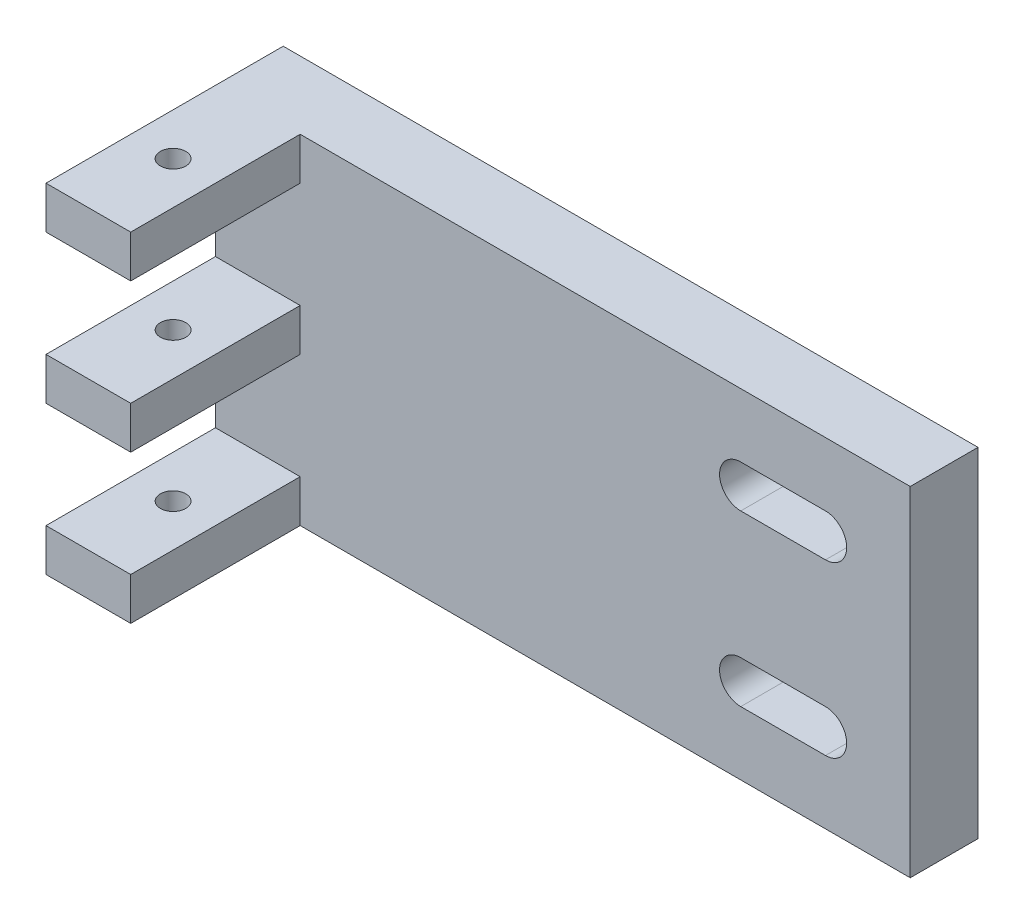
SolidWorks part; units mm, degrees
ref_plane "前视基准面" through (0, 0, 0) normal (0, 0, 1) x (1, 0, 0)
ref_plane "上视基准面" through (0, 0, 0) normal (0, 1, 0) x (1, 0, 0)
ref_plane "右视基准面" through (0, 0, 0) normal (1, 0, 0) x (0, 0, -1)
sketch "草图1" plane through (0, 0, 0) normal (0, 0, 1) x (1, 0, 0)
  line L0 (26.1842, 30.9079) -> (26.1842, -9.0921) construction
  line L1 (-25.8158, 30.9079) -> (46.1842, 30.9079)
  line L2 (-25.8158, 30.9079) -> (-25.8158, -9.0921)
  line L3 (-25.8158, -9.0921) -> (46.1842, -9.0921)
  line L4 (46.1842, 30.9079) -> (46.1842, -9.0921)
  line L7 (36.1842, 23.4079) -> (46.1842, 23.4079)
  line L8 (46.1842, 30.9079) -> (56.1842, 30.9079)
  line L9 (46.1842, 30.9079) -> (46.1842, -9.0921)
  line L10 (46.1842, -9.0921) -> (56.1842, -9.0921)
  line L11 (56.1842, 30.9079) -> (56.1842, -9.0921)
  line L12 (36.1842, 18.4079) -> (46.1842, 18.4079)
  line L13 (36.1842, 3.4079) -> (46.1842, 3.4079)
  line L14 (36.1842, -1.5921) -> (46.1842, -1.5921)
  circle A0 centre (36.1842, 20.9079) radius 2.5
  circle A1 centre (36.1842, 0.9079) radius 2.5
  circle A2 centre (46.1842, 20.9079) radius 2.5
  circle A3 centre (46.1842, 0.9079) radius 2.5
  dimension "D4" = 10
  dimension "D1" = 72
  dimension "D2" = 40
  dimension "D3" = 20
extrude "凸台-拉伸1" add sketch "草图1" along normal blind 8 contours L0 L1 L2 L3 | L1 L0 L3 L9 L14 A1 L13 L12 A0 L7 L4 | A3 L9 L10 L11 L8 L4 A2
sketch "草图3" plane through (0, 0, 8) normal (0, 0, 1) x (1, 0, 0)
  line L0 (-25.8158, 10.9079) -> (-25.8158, 13.4079) construction
  line L1 (-25.8158, 30.9079) -> (-15.8158, 30.9079)
  line L2 (-25.8158, 30.9079) -> (-25.8158, 25.9079)
  line L3 (-25.8158, 25.9079) -> (-15.8158, 25.9079)
  line L4 (-15.8158, 30.9079) -> (-15.8158, 25.9079)
  line L5 (-25.8158, -9.0921) -> (-15.8158, -9.0921)
  line L6 (-25.8158, -9.0921) -> (-25.8158, -4.0921)
  line L7 (-25.8158, -4.0921) -> (-15.8158, -4.0921)
  line L8 (-15.8158, -9.0921) -> (-15.8158, -4.0921)
  line L9 (-25.8158, 30.9079) -> (-25.8158, -9.0921) construction
  line L11 (-25.8158, 13.4079) -> (-15.8158, 13.4079)
  line L12 (-25.8158, 13.4079) -> (-25.8158, 8.4079)
  line L13 (-25.8158, 8.4079) -> (-15.8158, 8.4079)
  line L14 (-15.8158, 13.4079) -> (-15.8158, 8.4079)
  dimension "D1" = 5
  dimension "D2" = 10
  dimension "D3" = 10
  dimension "D4" = 5
  dimension "D5" = 2.5
  dimension "D6" = 5
  dimension "D7" = 10
extrude "凸台-拉伸3" add sketch "草图3" along normal blind 20 contours L2 L1 L4 L3 | L12 L11 L14 L13 | L6 L5 L8 L7
sketch "草图4" plane through (0, 30.9079, 0) normal (0, 1, 0) x (1, 0, 0)
  line L0 (-20.8158, -28) -> (-20.8158, -18) construction
  line L1 (-25.8158, -28) -> (-15.8158, -28) construction
  circle A0 centre (-20.8158, -18) radius 1.5
  dimension "D1" = 10
extrude "切除-拉伸1" cut sketch "草图4" against normal blind 47
